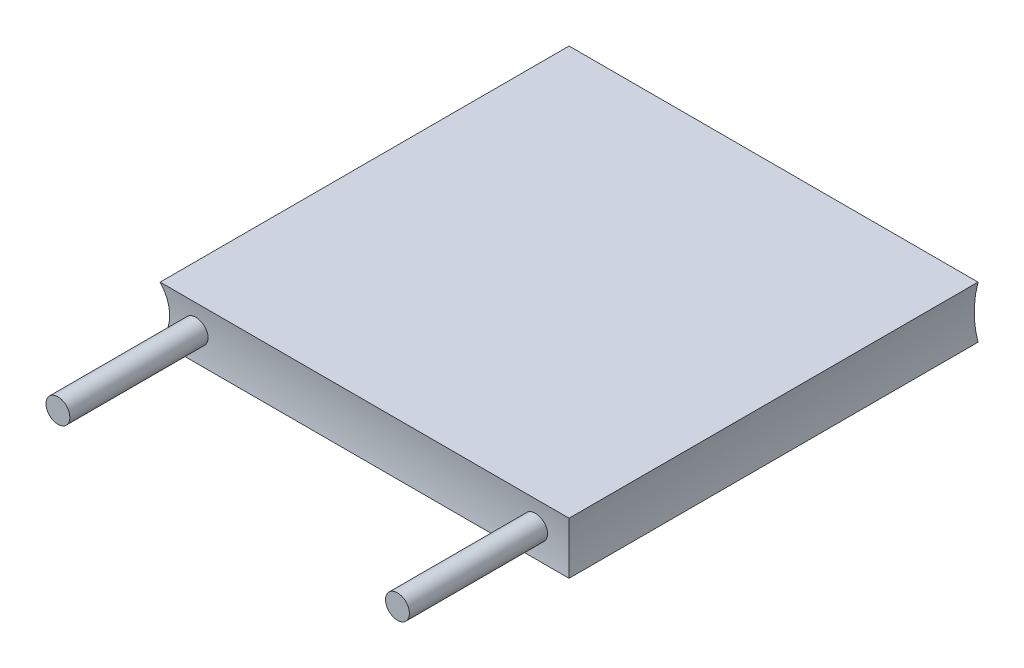
SolidWorks part; units mm, degrees
material "Ceramic Porcelain"
ref_plane "Front Plane" through (0, 0, 0) normal (0, 0, 1) x (1, 0, 0)
ref_plane "Top Plane" through (0, 0, 0) normal (0, 1, 0) x (1, 0, 0)
ref_plane "Right Plane" through (0, 0, 0) normal (1, 0, 0) x (0, 0, -1)
sketch "Sketch1" plane through (0, 0, 0) normal (0, 1, 0) x (1, 0, 0)
  line L1 (0, 0) -> (30, 0)
  line L2 (0, 0) -> (0, 30)
  line L3 (0, 30) -> (30, 30)
  line L4 (30, 0) -> (30, 30)
  dimension "D1" = 30
extrude "Boss-Extrude1" add sketch "Sketch1" along normal blind 3.82
sketch "Sketch2" plane through (0, 0, 0) normal (0, 0, 1) x (1, 0, 0)
  line L0 (0, 1.91) -> (-3, 1.91)
  line L1 (0, 3.82) -> (0, 0) construction
  line L2 (0, 0) -> (30, 0) construction
  line L3 (0, 3.82) -> (-3, 1.91)
  line L4 (0, 0) -> (-3, 1.91)
  line L5 (30, 1.91) -> (43, 1.91)
  line L6 (30, 3.82) -> (30, 0) construction
  line L7 (30, 3.82) -> (43, 1.91)
  line L8 (30, 0) -> (43, 1.91)
  arc A0 (0, 3.82) -> (0, 0) centre (-3, 1.91) cw
  arc A1 (30, 3.82) -> (30, 0) centre (43, 1.91) ccw
  line M6 (30, 0) -> (30, 3.82)
  line M8 (0, 3.82) -> (0, 0)
extrude "Cut-Extrude2" cut sketch "Sketch2" against normal through all contours L3 L0 M8 | A0 M8 | L4 L0 M8 | L7 L5 M6 | L8 L5 M6 | A1 M6
sketch "Sketch3" plane through (0, 0, 0) normal (1, 0, 0) x (0, 0, -1)
  line L0 (30, 1.91) -> (43, 1.91)
  line L1 (30, 0) -> (30, 3.82) construction
  line L2 (0, 1.91) -> (-13, 1.91)
  line L3 (0, 3.82) -> (0, 0) construction
  line L4 (30, 3.82) -> (43, 1.91)
  line L5 (30, 0) -> (43, 1.91)
  line L6 (0, 3.82) -> (-13, 1.91)
  line L7 (0, 0) -> (-13, 1.91)
  arc A0 (0, 3.82) -> (0, 0) centre (-13, 1.91) cw
  arc A1 (30, 3.82) -> (30, 0) centre (43, 1.91) ccw
extrude "Cut-Extrude5" cut sketch "Sketch3" along normal blind 45
sketch "Sketch4" plane through (0, 0, 0) normal (0, 0, 1) x (1, 0, 0)
  circle A0 centre (2.5, 1.91) radius 0.875
extrude "Boss-Extrude2" add sketch "Sketch4" along normal blind 10 and the other way blind 5
sketch "Sketch5" plane through (0, 0, 0) normal (0, 0, 1) x (1, 0, 0)
  circle A0 centre (27.4107, 1.91) radius 0.875
extrude "Boss-Extrude3" add sketch "Sketch5" along normal blind 10 and the other way blind 5
ref_plane "Plane1" through (0, 0, -15) normal (0, 0, 1) x (1, 0, 0)
ref_plane "Plane2" through (15, 0, 0) normal (1, 0, 0) x (0, 0, -1)
